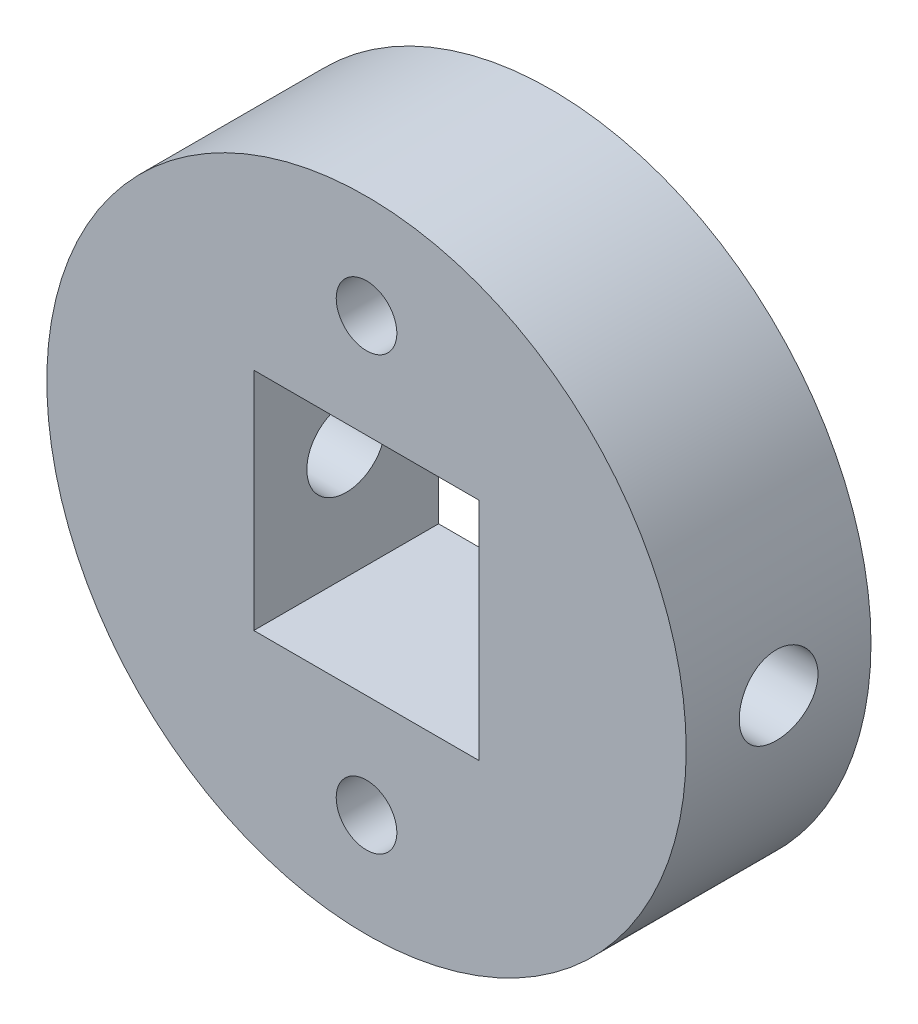
SolidWorks part; units mm, degrees
ref_plane "Front Plane" through (0, 0, 0) normal (0, 0, 1) x (1, 0, 0)
ref_plane "Top Plane" through (0, 0, 0) normal (0, 1, 0) x (1, 0, 0)
ref_plane "Right Plane" through (0, 0, 0) normal (1, 0, 0) x (0, 0, -1)
sketch "Sketch1" plane through (0, 0, 0) normal (0, 0, 1) x (1, 0, 0)
  line L1 (-3.8735, -3.8735) -> (3.8735, -3.8735)
  line L2 (-3.8735, -3.8735) -> (-3.8735, 3.8735)
  line L3 (-3.8735, 3.8735) -> (3.8735, 3.8735)
  line L4 (3.8735, -3.8735) -> (3.8735, 3.8735)
  line L5 (-3.8735, -3.8735) -> (3.8735, 3.8735) construction
  line L6 (-3.8735, 3.8735) -> (3.8735, -3.8735) construction
  circle A1 centre (0, 0) radius 10.9855
  dimension "D1" = 7.747
  dimension "D3" = 21.971
  dimension "D2" = 7.747
extrude "Boss-Extrude1" add sketch "Sketch1" along normal blind 6.35
ref_plane "Plane1" through (10.9855, 0, 0) normal (1, 0, 0) x (0, 0, -1)
sketch "Sketch3" plane through (3.8735, 0, 0) normal (-1, 0, 0) x (0, 0, 1)
  line L0 (3.175, 3.8735) -> (3.175, -3.8735) construction
  line L1 (6.35, 3.8735) -> (0, 3.8735) construction
  line L2 (6.35, -3.8735) -> (0, -3.8735) construction
  point P0 (3.175, 0)
sketch "Sketch4" plane through (10.9855, 0, 0) normal (1, 0, 0) x (0, 0, -1)
  point P0 (-3.175, 0)
ref_plane "Plane2" through (-10.9855, 0, 0) normal (-1, 0, 0) x (0, 0, 1)
sketch "Sketch5" plane through (-10.9855, 0, 0) normal (-1, 0, 0) x (0, 0, 1)
  point P0 (3.175, 0)
hole_wizard "#6-32 Tapped Hole1" positions "3DSketch2" profile "Sketch7" tap size "#6-32" standard "ANSI Inch"
sketch3d "3DSketch2"
  point P0 (10.9855, 0, 3.175)
  point P3 (10.9855, 0, 3.175)
  point P5 (10.9855, 0, 3.175)
  point P7 (10.9855, 0, 3.175)
  point P9 (10.9855, 0, 3.175)
  point P11 (10.9855, 0, 3.175)
  point P13 (10.9855, 0, 3.175)
  point P15 (3.8735, 0, 3.175)
sketch "Sketch7" plane through (3.8735, 0, 3.175) normal (0, 1, 0) x (0, 0, 1)
  line L0 (0, 0) -> (0, 7.112)
  line L1 (0, 7.112) -> (1.3525, 7.112)
  line L2 (1.3525, 7.112) -> (1.3525, 0)
  line L5 (1.3525, 0) -> (0, 0)
  line L11 (0, -6.35) -> (0, 107.95) construction
  dimension "Thru Tap Drill Dia." = 2.7051
  dimension "Thru Tap Drill Depth" = 7.112
cosmetic thread "Hole Thread1" parameters "D2"=3.5052
cosmetic thread "Hole Thread2" parameters "D2"=3.5052
cosmetic thread "Hole Thread3" parameters "D2"=3.5052
cosmetic thread "Hole Thread4" parameters "D2"=3.5052
cosmetic thread "Hole Thread5" parameters "D2"=3.5052
cosmetic thread "Hole Thread6" parameters "D2"=3.5052
cosmetic thread "Hole Thread7" parameters "D2"=3.5052
cosmetic thread "Hole Thread8" parameters "D2"=3.5052
sketch "Sketch9" plane through (-3.8735, 0, 0) normal (1, 0, 0) x (0, 0, -1)
  point P0 (-3.175, 0)
hole_wizard "#6-32 Tapped Hole2" positions "Sketch10" profile "Sketch11" tap size "#6-32" standard "ANSI Inch" end condition through all
sketch "Sketch10" plane through (-3.8735, 0, 0) normal (1, 0, 0) x (0, 0, -1)
  point P0 (-3.175, 0)
sketch "Sketch11" plane through (-3.8735, 0, 3.175) normal (0, 1, 0) x (0, 0, -1)
  line L0 (0, 0) -> (0, 7.112)
  line L1 (0, 7.112) -> (1.3525, 7.112)
  line L2 (1.3525, 7.112) -> (1.3525, 0)
  line L5 (1.3525, 0) -> (0, 0)
  line L11 (0, -6.35) -> (0, 107.95) construction
  dimension "Thru Tap Drill Dia." = 2.7051
  dimension "Thru Tap Drill Depth" = 7.112
cosmetic thread "Hole Thread9" parameters "D2"=3.5052
sketch "Sketch12" plane through (0, 0, 0) normal (0, 0, -1) x (-1, 0, 0)
  line L2 (3.8735, -3.8735) -> (-3.8735, -3.8735) construction
  line L3 (0, -3.8735) -> (0, -10.9855) construction
  line L4 (-10.9855, 0) -> (10.9855, 0) construction
  circle A0 centre (0, 0) radius 10.9855 construction
  point P2 (0, -7.4295)
  point P4 (0, -3.8735)
  point P6 (0, 7.4295)
hole_wizard "#45 (0.082) Diameter Hole1" positions "Sketch15" profile "Sketch16" hole size "#45" standard "ANSI Inch" end condition through all
sketch "Sketch15" plane through (0, 0, 0) normal (0, 0, -1) x (-1, 0, 0)
  point P0 (0, -7.4295)
  point P3 (0, 7.4295)
sketch "Sketch16" plane through (0, -7.4295, 0) normal (1, 0, 0) x (0, 1, 0)
  line L0 (0, 0) -> (0, 6.35)
  line L1 (0, 6.35) -> (1.0414, 6.35)
  line L2 (1.0414, 6.35) -> (1.0414, 0)
  line L5 (1.0414, 0) -> (0, 0)
  line L11 (0, -6.35) -> (0, 107.95) construction
  dimension "Thru Hole Dia." = 2.0828
  dimension "Thru Hole Depth" = 6.35
sketch "Sketch17" plane through (0, 0, 6.35) normal (0, 0, 1) x (1, 0, 0)
  circle A0 centre (0, 0) radius 10.9855 construction
  point P0 (0, 10.9855)
